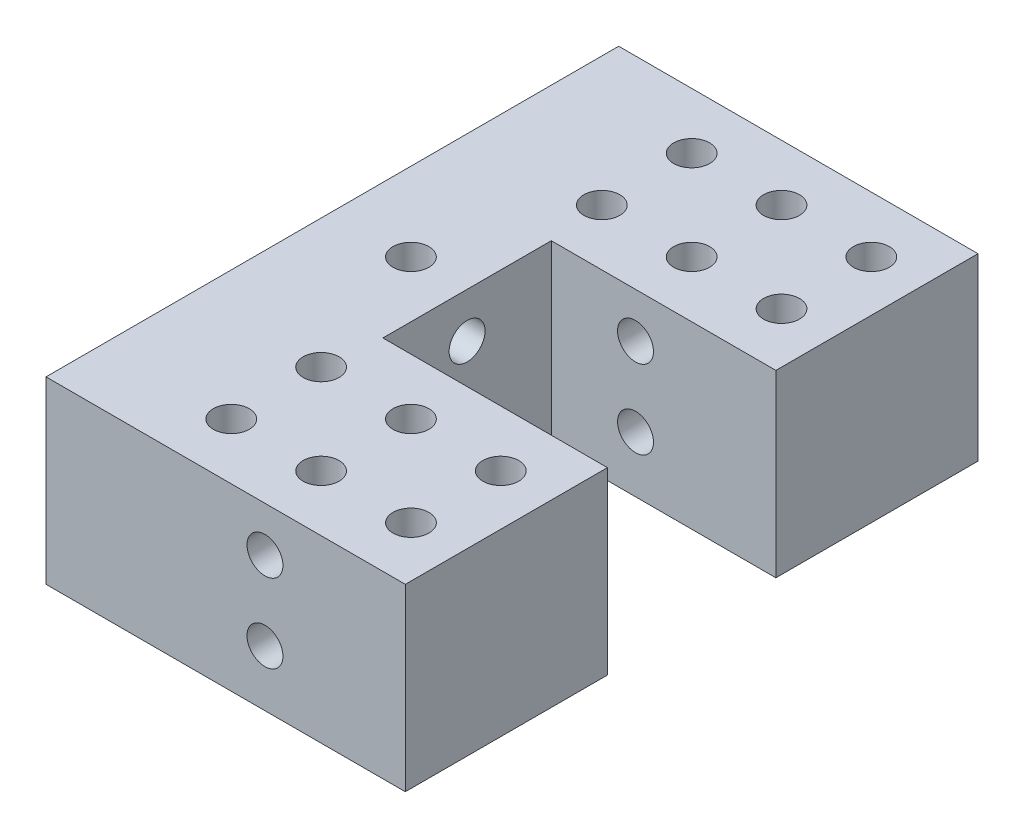
SolidWorks part; units mm, degrees
ref_plane "前视基准面" through (0, 0, 0) normal (0, 0, 1) x (1, 0, 0)
ref_plane "上视基准面" through (0, 0, 0) normal (0, 1, 0) x (1, 0, 0)
ref_plane "右视基准面" through (0, 0, 0) normal (1, 0, 0) x (0, 0, -1)
other "Configuration Table"
sketch "草图1" plane through (0, 0, 0) normal (0, 1, 0) x (1, 0, 0)
  line L0 (0, 0) -> (32, 0)
  line L1 (32, 0) -> (32, -18)
  line L2 (32, -18) -> (12, -18)
  line L3 (12, -18) -> (12, -33)
  line L4 (12, -33) -> (32, -33)
  line L5 (32, -33) -> (32, -51)
  line L6 (32, -51) -> (0, -51)
  line L7 (0, -51) -> (0, 0)
  line L8 (19.5, -18) -> (19.5, -16.1208) construction
  line L9 (12, -25.5) -> (16.2187, -25.5) construction
  circle A0 centre (19.5, -13) radius 1.6
  circle A1 centre (19.5, -5) radius 1.6
  circle A2 centre (27.5, -5) radius 1.6
  circle A3 centre (27.5, -13) radius 1.6
  circle A4 centre (11.5, -5) radius 1.6
  circle A5 centre (11.5, -13) radius 1.6
  circle A6 centre (27.5, -38) radius 1.6
  circle A7 centre (19.5, -38) radius 1.6
  circle A8 centre (11.5, -38) radius 1.6
  circle A9 centre (27.5, -46) radius 1.6
  circle A10 centre (19.5, -46) radius 1.6
  circle A11 centre (11.5, -46) radius 1.6
  circle A12 centre (7, -25.5) radius 1.6
  point P10 (22, -18)
  point P13 (12, -25.5)
  dimension "D6" = 3.2
  dimension "D13" = 3.2
  dimension "D1" = 15
  dimension "D2" = 18
  dimension "D3" = 12
  dimension "D4" = 5
  dimension "D5" = 8
  dimension "D8" = 20
  dimension "D9" = 7.5
  dimension "D10" = 8
  dimension "D12" = 8
  dimension "D14" = 5
  dimension "D7" = 2
  dimension "D11" = 2
extrude "凸台-拉伸1" add sketch "草图1" along normal blind 16
sketch "草图2" plane through (0, 0, 51) normal (0, 0, 1) x (1, 0, 0)
  line L0 (19.5, 17.2049) -> (19.5, -1.0587) construction
  line L1 (32, 16) -> (32, 0) construction
  line L2 (0, 0) -> (32, 0) construction
  circle A0 centre (19.5, 12) radius 1.6
  circle A1 centre (19.5, 5) radius 1.6
  dimension "D2" = 3.2
  dimension "D1" = 12.5
  dimension "D3" = 5
  dimension "D4" = 7
extrude "切除-拉伸1" cut sketch "草图2" against normal up to surface (51 mm away) up to face at (16, 8, 0)
sketch "草图3" plane through (0, 0, 0) normal (-1, 0, 0) x (0, 0, 1)
  line L0 (25.5, 21.3258) -> (25.5, -5.8572) construction
  line L1 (51, 16) -> (51, 0) construction
  line L2 (0, 0) -> (51, 0) construction
  circle A0 centre (25.5, 5) radius 1.6
  circle A1 centre (25.5, 12) radius 1.6
  dimension "D2" = 3.2
  dimension "D1" = 25.5
  dimension "D3" = 5
  dimension "D4" = 7
extrude "切除-拉伸2" cut sketch "草图3" against normal up to surface (12 mm away) up to face at (12, 8, 25.5)
